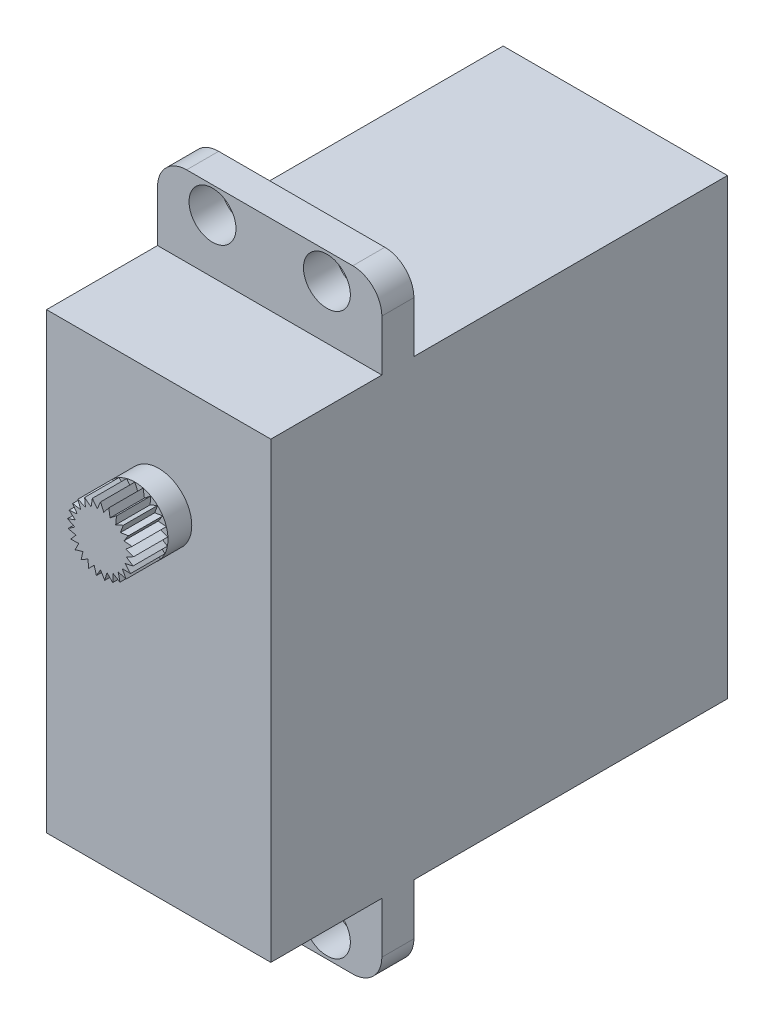
SolidWorks part; units mm, degrees
ref_plane "Front Plane" through (0, 0, 0) normal (0, 0, 1) x (1, 0, 0)
ref_plane "Top Plane" through (0, 0, 0) normal (0, 1, 0) x (1, 0, 0)
ref_plane "Right Plane" through (0, 0, 0) normal (1, 0, 0) x (0, 0, -1)
sketch "Sketch1" plane through (0, 0, 0) normal (0, 0, 1) x (1, 0, 0)
  line L1 (0, 0) -> (19.6, 0)
  line L2 (0, 0) -> (0, -39.6)
  line L3 (0, -39.6) -> (19.6, -39.6)
  line L4 (19.6, 0) -> (19.6, -39.6)
  dimension "D1" = 19.6
  dimension "D2" = 39.6
extrude "Boss-Extrude1" add sketch "Sketch1" along normal blind 39.9
sketch "Sketch2" plane through (0, 0, 39.9) normal (0, 0, 1) x (1, 0, 0)
  line L2 (19.6, 0) -> (0, 0) construction
  circle A0 centre (9.8, -10) radius 2.89
  point P5 (9.8, 0)
  dimension "D1" = 5.78
  dimension "D2" = 10
extrude "Boss-Extrude2" add sketch "Sketch2" along normal blind 5.08
ref_plane "Plane1" through (0, 0, 27.4) normal (0, 0, 1) x (1, 0, 0)
sketch "Sketch3" plane through (0, 0, 27.4) normal (0, 0, 1) x (1, 0, 0)
  line L0 (19.6, 0) -> (0, 0) construction
  line L1 (0, 7) -> (19.6, 7)
  line L2 (0, 7) -> (0, -46.6)
  line L3 (0, -46.6) -> (19.6, -46.6)
  line L4 (19.6, 7) -> (19.6, -46.6)
  line L5 (0, 0) -> (0, -39.6) construction
  point P6 (9.8, 0)
  point P7 (9.8, 7)
  point P8 (0, -19.8)
  point P11 (0, -19.8)
  dimension "D1" = 19.6
  dimension "D2" = 53.6
extrude "Boss-Extrude3" add sketch "Sketch3" along normal blind 2.8 contours L2 L1 L4 L3
sketch "Sketch4" plane through (0, 0, 30.2) normal (0, 0, 1) x (1, 0, 0)
  line L0 (4.8, 4.7) -> (14.8, -44.3) construction
  line L1 (19.6, -39.6) -> (19.6, 0) construction
  line L2 (14.8, 4.7) -> (4.8, -44.3) construction
  line L3 (0, 7) -> (19.6, 7) construction
  circle A0 centre (4.8, 4.7) radius 2.05
  circle A1 centre (14.8, 4.7) radius 2.05
  circle A2 centre (4.8, -44.3) radius 2.05
  circle A3 centre (14.8, -44.3) radius 2.05
  point P8 (9.8, -19.8)
  point P11 (19.6, -19.8)
  point P14 (9.8, 7)
  dimension "D3" = 4.1
  dimension "D1" = 10
  dimension "D2" = 49
extrude "Cut-Extrude1" cut sketch "Sketch4" against normal through all
fillet "Fillet1" radius 2.54 4 edges at (19.6, 7, 28.8) (0, 7, 28.8) (0, -46.6, 28.8) (19.6, -46.6, 28.8)
sketch "Sketch5" plane through (0, 0, 44.98) normal (0, 0, 1) x (1, 0, 0)
  line L0 (9.8, -7.11) -> (9.518, -7.7677)
  line L1 (9.518, -7.7677) -> (9.8, -7.11)
  line L2 (9.8, -7.11) -> (10.082, -7.7677)
  line L3 (10.5187, -7.2008) -> (10.082, -7.7677)
  line L4 (10.5187, -7.2008) -> (10.6283, -7.908)
  line L5 (11.1923, -7.4675) -> (10.6283, -7.908)
  line L6 (11.1923, -7.4675) -> (11.1225, -8.1797)
  line L7 (11.7783, -7.8933) -> (11.1225, -8.1797)
  line L8 (11.7783, -7.8933) -> (11.5337, -8.5658)
  line L9 (12.2401, -8.4515) -> (11.5337, -8.5658)
  line L10 (12.2401, -8.4515) -> (11.8359, -9.042)
  line L11 (12.5486, -9.1069) -> (11.8359, -9.042)
  line L12 (12.5486, -9.1069) -> (12.0101, -9.5784)
  line L13 (12.6843, -9.8185) -> (12.0101, -9.5784)
  line L14 (12.6843, -9.8185) -> (12.0456, -10.1413)
  line L15 (12.6388, -10.5415) -> (12.0456, -10.1413)
  line L16 (12.6388, -10.5415) -> (11.9399, -10.6953)
  line L17 (12.415, -11.2305) -> (11.9399, -10.6953)
  line L18 (12.415, -11.2305) -> (11.6997, -11.2056)
  line L19 (12.0268, -11.8422) -> (11.6997, -11.2056)
  line L20 (12.0268, -11.8422) -> (11.3402, -11.6402)
  line L21 (11.4987, -12.3381) -> (11.3402, -11.6402)
  line L22 (11.4987, -12.3381) -> (10.8839, -11.9717)
  line L23 (10.8639, -12.6871) -> (10.8839, -11.9717)
  line L24 (10.8639, -12.6871) -> (10.3596, -12.1793)
  line L25 (10.1622, -12.8672) -> (10.3596, -12.1793)
  line L26 (10.1622, -12.8672) -> (9.8, -12.25)
  line L27 (9.4378, -12.8672) -> (9.8, -12.25)
  line L28 (9.4378, -12.8672) -> (9.2404, -12.1793)
  line L29 (8.7361, -12.6871) -> (9.2404, -12.1793)
  line L30 (8.7361, -12.6871) -> (8.7161, -11.9717)
  line L31 (8.1013, -12.3381) -> (8.7161, -11.9717)
  line L32 (8.1013, -12.3381) -> (8.2598, -11.6402)
  line L33 (7.5732, -11.8422) -> (8.2598, -11.6402)
  line L34 (7.5732, -11.8422) -> (7.9003, -11.2056)
  line L35 (7.185, -11.2305) -> (7.9003, -11.2056)
  line L36 (7.185, -11.2305) -> (7.6601, -10.6953)
  line L37 (6.9612, -10.5415) -> (7.6601, -10.6953)
  line L38 (6.9612, -10.5415) -> (7.5544, -10.1413)
  line L39 (6.9157, -9.8185) -> (7.5544, -10.1413)
  line L40 (6.9157, -9.8185) -> (7.5899, -9.5784)
  line L41 (7.0514, -9.1069) -> (7.5899, -9.5784)
  line L42 (7.0514, -9.1069) -> (7.7641, -9.042)
  line L43 (7.3599, -8.4515) -> (7.7641, -9.042)
  line L44 (7.3599, -8.4515) -> (8.0663, -8.5658)
  line L45 (7.8217, -7.8933) -> (8.0663, -8.5658)
  line L46 (7.8217, -7.8933) -> (8.4775, -8.1797)
  line L47 (8.4077, -7.4675) -> (8.4775, -8.1797)
  line L48 (8.4077, -7.4675) -> (8.9717, -7.908)
  line L49 (9.0813, -7.2008) -> (8.9717, -7.908)
  line L50 (9.0813, -7.2008) -> (9.518, -7.7677)
  circle A0 centre (9.8, -10) radius 2.89 construction
  circle A1 centre (9.8, -10) radius 2.89 construction
  circle A2 centre (9.8, -10) radius 2.25 construction
  point P84 (9.8, -10)
  circle M3 centre (9.8, -10) radius 2.89
  dimension "D1" = 4.5
  dimension "D2" = 14.4
  dimension "D3" = 25
extrude "Cut-Extrude3" cut sketch "Sketch5" against normal blind 3 contours L3 L2 M3 | L50 L0 M3 | L49 L48 M3 | L47 L46 M3 | L45 L44 M3 | L43 L42 M3 | L41 L40 M3 | L39 L38 M3 | L37 L36 M3 | L7 L6 M3 | L5 L4 M3 | L9 L8 M3 | L11 L10 M3 | L13 L12 M3 | L15 L14 M3 | L17 L16 M3 | L19 L18 M3 | L21 L20 M3 | L23 L22 M3 | L25 L24 M3 | L27 L26 M3 | L29 L28 M3 | L31 L30 M3 | L33 L32 M3 | L35 L34 M3
